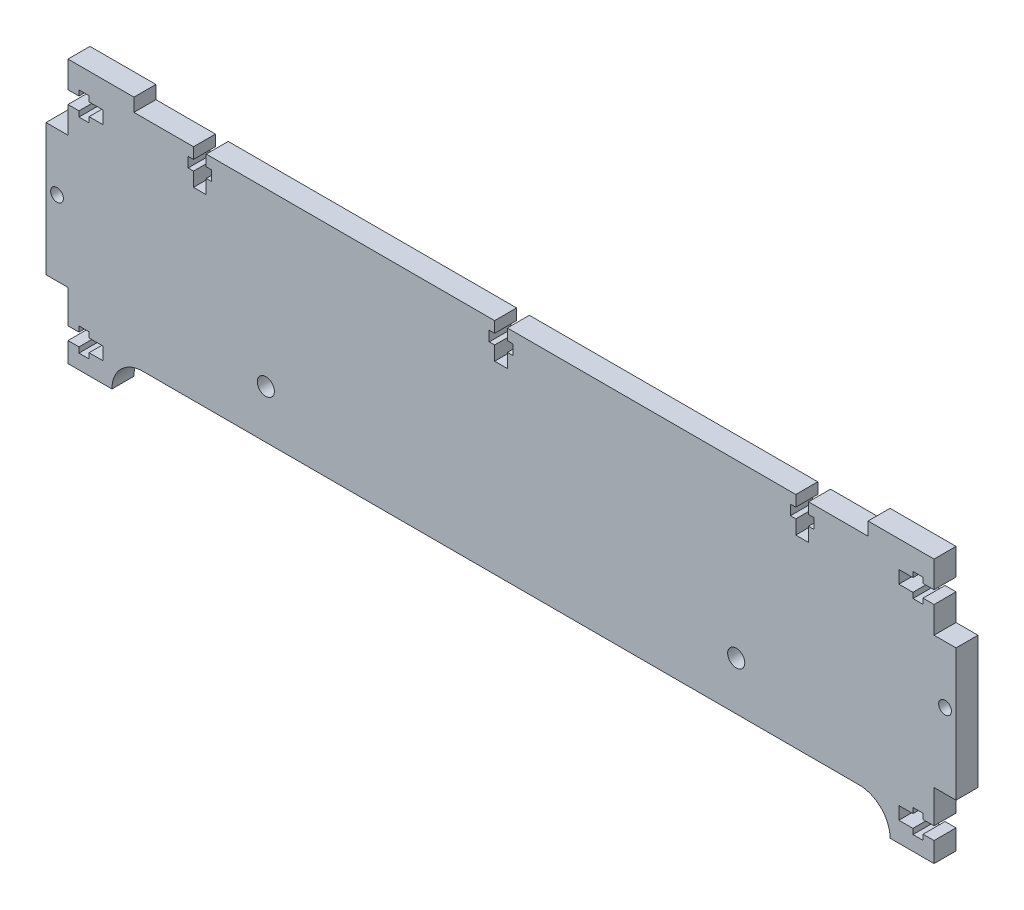
SolidWorks part; units mm, degrees
ref_plane "Front Plane" through (0, 0, 0) normal (0, 0, 1) x (1, 0, 0)
ref_plane "Top Plane" through (0, 0, 0) normal (0, 1, 0) x (1, 0, 0)
ref_plane "Right Plane" through (0, 0, 0) normal (1, 0, 0) x (0, 0, -1)
sketch "Sketch1" plane through (0, 0, 0) normal (0, 0, 1) x (1, 0, 0)
  line L1 (-103.5, 51) -> (103.5, 51)
  line L2 (-103.5, 51) -> (-103.5, -9)
  line L3 (-103.5, -9) -> (103.5, -9)
  line L4 (103.5, 51) -> (103.5, -9)
  point P6 (0, 0)
  point P7 (0, 0)
extrude "Boss-Extrude1" add sketch "Sketch1" along normal blind 5
sketch "Sketch2" plane through (0, 0, 5) normal (0, 0, 1) x (1, 0, 0)
  line L0 (103.5, -9) -> (103.5, 51) construction
  line L1 (-103.5, 51) -> (-98.5, 51)
  line L2 (-103.5, 51) -> (-103.5, 36)
  line L3 (-103.5, 36) -> (-98.5, 36)
  line L4 (-98.5, 51) -> (-98.5, 36)
  line L5 (-103.5, -9) -> (-98.5, -9)
  line L6 (-103.5, -9) -> (-103.5, 6)
  line L7 (-103.5, 6) -> (-98.5, 6)
  line L8 (-98.5, -9) -> (-98.5, 6)
  line L9 (98.5, 36) -> (103.5, 36)
  line L10 (98.5, 36) -> (98.5, 51)
  line L11 (98.5, 51) -> (103.5, 51)
  line L12 (103.5, 36) -> (103.5, 51)
  line L13 (103.5, 6) -> (98.5, 6)
  line L14 (103.5, 6) -> (103.5, -9)
  line L15 (103.5, -9) -> (98.5, -9)
  line L16 (98.5, 6) -> (98.5, -9)
  line L17 (-103.5, -9) -> (103.5, -9) construction
  line L19 (-98.5, 6) -> (98.5, 6) construction
  point P26 (0, 0)
  point P27 (103.5, 36)
  point P28 (0, 0)
  point P29 (0, 0)
  point P31 (98.5, 36)
  point P33 (98.5, 6)
extrude "Cut-Extrude1" cut sketch "Sketch2" against normal through all
sketch "Sketch3" plane through (0, 0, 5) normal (0, 0, 1) x (1, 0, 0)
  line L0 (98.5, 51) -> (-98.5, 51) construction
  line L1 (-83.5, 51) -> (83.5, 51)
  line L2 (-83.5, 51) -> (-83.5, 48)
  line L3 (-83.5, 48) -> (83.5, 48)
  line L4 (83.5, 51) -> (83.5, 48)
  line L5 (-103.5, 36) -> (-103.5, 6) construction
  line L6 (103.5, 6) -> (103.5, 36) construction
  line L7 (-98.5, -9) -> (98.5, -9) construction
  line L8 (-81.5, -9) -> (81.5, -9)
  line L9 (-81.5, -9) -> (-81.5, -2)
  line L10 (-81.5, -2) -> (81.5, -2)
  line L11 (81.5, -9) -> (81.5, -2)
  circle A0 centre (-81.5, -9) radius 7
  circle A1 centre (81.5, -9) radius 7
  line M9 (-98.5, -9) -> (98.5, -9)
  line M15 (98.5, 51) -> (-98.5, 51)
  dimension "D4" = 7
  dimension "D1" = 3
  dimension "D2" = 20
  dimension "D3" = 20
  dimension "D5" = 15
  dimension "D6" = 15
extrude "Cut-Extrude2" cut sketch "Sketch3" against normal blind 5 contours L4 L2 L3 M15 | A1 L10 A0 L8 | A0 L9 M9 | L9 A0 M9 | L11 A1 M9 | A1 L11 M9
sketch "Sketch4" plane through (0, 0, 5) normal (0, 0, 1) x (1, 0, 0)
  line L4 (98.5, 44.95) -> (90.5, 44.95)
  line L5 (90.5, 44.95) -> (90.5, 42.05)
  line L6 (90.5, 42.05) -> (98.5, 42.05)
  line L7 (98.5, 42.05) -> (98.5, 44.95)
  line L8 (98.5, 44.95) -> (90.5, 44.95)
  line L9 (90.5, 44.95) -> (90.5, 42.05)
  line L10 (90.5, 42.05) -> (98.5, 42.05)
  line L11 (98.5, 42.05) -> (98.5, 44.95)
  line L12 (98.5, -1.55) -> (90.5, -1.55)
  line L13 (90.5, -1.55) -> (90.5, -4.45)
  line L14 (90.5, -4.45) -> (98.5, -4.45)
  line L15 (98.5, -4.45) -> (98.5, -1.55)
  line L16 (98.5, -1.55) -> (90.5, -1.55)
  line L17 (90.5, -1.55) -> (90.5, -4.45)
  line L18 (90.5, -4.45) -> (98.5, -4.45)
  line L19 (98.5, -4.45) -> (98.5, -1.55)
  line L20 (96, 46.175) -> (93.7, 46.175)
  line L21 (96, 40.825) -> (96, 46.175)
  line L22 (93.7, 40.825) -> (96, 40.825)
  line L23 (93.7, 46.175) -> (93.7, 40.825)
  line L24 (96, 46.175) -> (93.7, 46.175)
  line L25 (96, 40.825) -> (96, 46.175)
  line L26 (93.7, 40.825) -> (96, 40.825)
  line L27 (93.7, 46.175) -> (93.7, 40.825)
  line L28 (96, -0.325) -> (93.7, -0.325)
  line L29 (96, -5.675) -> (96, -0.325)
  line L30 (93.7, -5.675) -> (96, -5.675)
  line L31 (93.7, -0.325) -> (93.7, -5.675)
  line L32 (96, -0.325) -> (93.7, -0.325)
  line L33 (96, -5.675) -> (96, -0.325)
  line L34 (93.7, -5.675) -> (96, -5.675)
  line L35 (93.7, -0.325) -> (93.7, -5.675)
  line L36 (-96, -5.675) -> (-93.7, -5.675)
  line L37 (-96, -0.325) -> (-96, -5.675)
  line L38 (-93.7, -0.325) -> (-96, -0.325)
  line L39 (-93.7, -5.675) -> (-93.7, -0.325)
  line L40 (-96, -5.675) -> (-93.7, -5.675)
  line L41 (-96, -0.325) -> (-96, -5.675)
  line L42 (-93.7, -0.325) -> (-96, -0.325)
  line L43 (-93.7, -5.675) -> (-93.7, -0.325)
  line L44 (71.175, 45.5) -> (65.825, 45.5)
  line L45 (71.175, 43.2) -> (71.175, 45.5)
  line L46 (65.825, 43.2) -> (71.175, 43.2)
  line L47 (65.825, 45.5) -> (65.825, 43.2)
  line L48 (71.175, 45.5) -> (65.825, 45.5)
  line L49 (71.175, 43.2) -> (71.175, 45.5)
  line L50 (65.825, 43.2) -> (71.175, 43.2)
  line L51 (65.825, 45.5) -> (65.825, 43.2)
  line L52 (69.95, 48) -> (67.05, 48)
  line L53 (69.95, 40) -> (69.95, 48)
  line L54 (67.05, 40) -> (69.95, 40)
  line L55 (67.05, 48) -> (67.05, 40)
  line L56 (69.95, 48) -> (67.05, 48)
  line L57 (69.95, 40) -> (69.95, 48)
  line L58 (67.05, 40) -> (69.95, 40)
  line L59 (67.05, 48) -> (67.05, 40)
  line L60 (-90.5, 42.05) -> (-90.5, 44.95)
  line L61 (-98.5, 42.05) -> (-90.5, 42.05)
  line L62 (-98.5, 44.95) -> (-98.5, 42.05)
  line L63 (-90.5, 44.95) -> (-98.5, 44.95)
  line L64 (-90.5, 42.05) -> (-90.5, 44.95)
  line L65 (-98.5, 42.05) -> (-90.5, 42.05)
  line L66 (-98.5, 44.95) -> (-98.5, 42.05)
  line L67 (-90.5, 44.95) -> (-98.5, 44.95)
  line L68 (-93.7, 40.825) -> (-93.7, 46.175)
  line L69 (-96, 40.825) -> (-93.7, 40.825)
  line L70 (-96, 46.175) -> (-96, 40.825)
  line L71 (-93.7, 46.175) -> (-96, 46.175)
  line L72 (-93.7, 40.825) -> (-93.7, 46.175)
  line L73 (-96, 40.825) -> (-93.7, 40.825)
  line L74 (-96, 46.175) -> (-96, 40.825)
  line L75 (-93.7, 46.175) -> (-96, 46.175)
  line L76 (-98.5, -4.45) -> (-90.5, -4.45)
  line L77 (-98.5, -1.55) -> (-98.5, -4.45)
  line L78 (-90.5, -1.55) -> (-98.5, -1.55)
  line L79 (-90.5, -4.45) -> (-90.5, -1.55)
  line L80 (-98.5, -4.45) -> (-90.5, -4.45)
  line L81 (-98.5, -1.55) -> (-98.5, -4.45)
  line L82 (-90.5, -1.55) -> (-98.5, -1.55)
  line L83 (-90.5, -4.45) -> (-90.5, -1.55)
  line L84 (2.675, 45.5) -> (-2.675, 45.5)
  line L85 (2.675, 43.2) -> (2.675, 45.5)
  line L86 (-2.675, 43.2) -> (2.675, 43.2)
  line L87 (-2.675, 45.5) -> (-2.675, 43.2)
  line L88 (2.675, 45.5) -> (-2.675, 45.5)
  line L89 (2.675, 43.2) -> (2.675, 45.5)
  line L90 (-2.675, 43.2) -> (2.675, 43.2)
  line L91 (-2.675, 45.5) -> (-2.675, 43.2)
  line L92 (1.45, 48) -> (-1.45, 48)
  line L93 (1.45, 40) -> (1.45, 48)
  line L94 (-1.45, 40) -> (1.45, 40)
  line L95 (-1.45, 48) -> (-1.45, 40)
  line L96 (1.45, 48) -> (-1.45, 48)
  line L97 (1.45, 40) -> (1.45, 48)
  line L98 (-1.45, 40) -> (1.45, 40)
  line L99 (-1.45, 48) -> (-1.45, 40)
  line L100 (-69.95, 40) -> (-67.05, 40)
  line L101 (-69.95, 48) -> (-69.95, 40)
  line L102 (-67.05, 48) -> (-69.95, 48)
  line L103 (-67.05, 40) -> (-67.05, 48)
  line L104 (-69.95, 40) -> (-67.05, 40)
  line L105 (-69.95, 48) -> (-69.95, 40)
  line L106 (-67.05, 48) -> (-69.95, 48)
  line L107 (-67.05, 40) -> (-67.05, 48)
  line L108 (-65.825, 43.2) -> (-65.825, 45.5)
  line L109 (-71.175, 43.2) -> (-65.825, 43.2)
  line L110 (-71.175, 45.5) -> (-71.175, 43.2)
  line L111 (-65.825, 45.5) -> (-71.175, 45.5)
  line L112 (-65.825, 43.2) -> (-65.825, 45.5)
  line L113 (-71.175, 43.2) -> (-65.825, 43.2)
  line L114 (-71.175, 45.5) -> (-71.175, 43.2)
  line L115 (-65.825, 45.5) -> (-71.175, 45.5)
  circle A1 centre (101, 23) radius 1.45
  circle A2 centre (101, 23) radius 1.45
  circle A3 centre (-101, 23) radius 1.45
  circle A4 centre (-101, 23) radius 1.45
  circle A5 centre (-53.5, 9) radius 1.95
  circle A6 centre (-53.5, 9) radius 1.95
  circle A7 centre (53.5, 9) radius 1.95
  circle A8 centre (53.5, 9) radius 1.95
  point P62 (0, 0)
  point P63 (0, 0)
  dimension "D1" = 0
  dimension "D2" = 0
  dimension "D3" = 0
  dimension "D4" = 0
  dimension "D5" = 0
  dimension "D6" = 0
  dimension "D7" = 0
  dimension "D8" = 0
  dimension "D9" = 0
  dimension "D10" = 0
  dimension "D11" = 0
  dimension "D12" = 0
  dimension "D13" = 0
  dimension "D14" = 0
  dimension "D15" = 0
  dimension "D16" = 0
  dimension "D17" = 0
  dimension "D18" = 0
extrude "Cut-Extrude3" cut sketch "Sketch4" against normal through all contours A4 | L65 L64 L67 L66 | L73 L72 L75 L74 | L80 L83 L82 L81 | L40 L43 L42 L41 | L104 L107 L106 L105 | L113 L112 L115 L114 | A6 | L98 L97 L96 L99 | L90 L89 L88 L91 | A8 | A2 | L16 L17 L18 L19 | L32 L35 L34 L33 | L10 L11 L8 L9 | L26 L25 L24 L27 | L58 L57 L56 L59 | L50 L49 L48 L51
